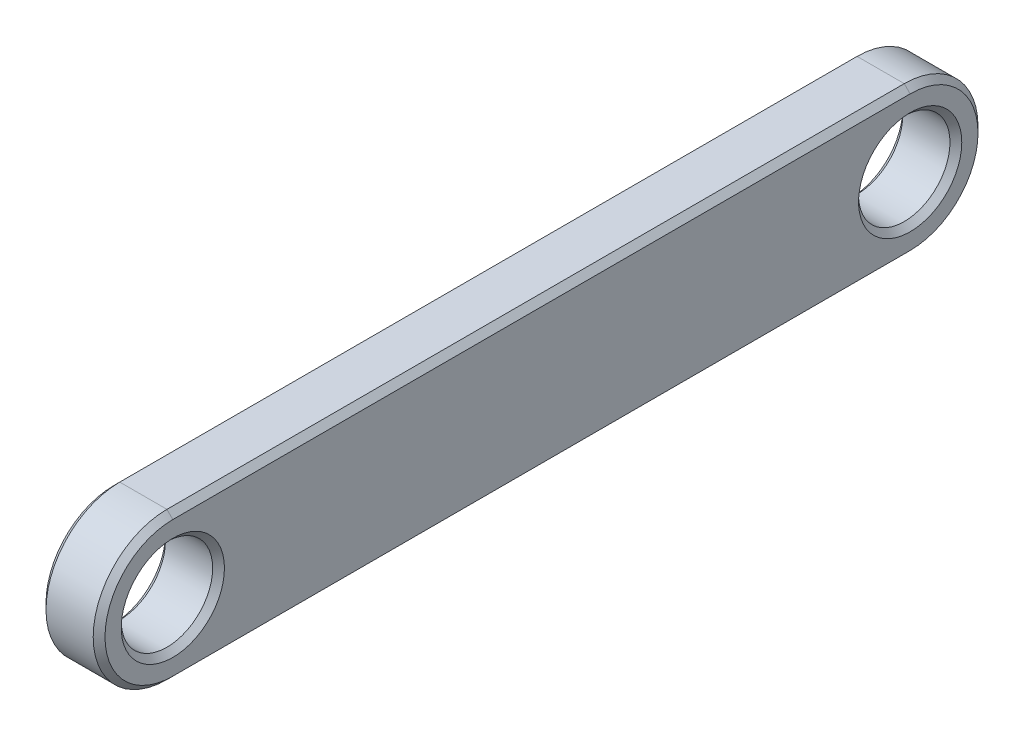
SolidWorks part; units mm, degrees
ref_plane "Front Plane" through (0, 0, 0) normal (0, 0, 1) x (1, 0, 0)
ref_plane "Top Plane" through (0, 0, 0) normal (0, 1, 0) x (1, 0, 0)
ref_plane "Right Plane" through (0, 0, 0) normal (1, 0, 0) x (0, 0, -1)
sketch "Sketch1" plane through (0, 0, 0) normal (1, 0, 0) x (0, 0, -1)
  line L0 (-12.5, 0) -> (12.5, 0) construction
  line L1 (-12.5, 2.5) -> (12.5, 2.5)
  line L2 (-12.5, -2.5) -> (12.5, -2.5)
  arc A0 (-12.5, 2.5) -> (-12.5, -2.5) centre (-12.5, 0) ccw
  arc A1 (12.5, -2.5) -> (12.5, 2.5) centre (12.5, 0) ccw
  circle A2 centre (-12.5, 0) radius 1.55
  circle A3 centre (12.5, 0) radius 1.55
  point P3 (0, 0)
  dimension "D1" = 3.1
  dimension "D2" = 3.1
  dimension "D4" = 2.5
  dimension "D3" = 25
extrude "Boss-Extrude1" add sketch "Sketch1" along normal blind 2
chamfer "Chamfer1" distance 0.2 angle 45 12 edges at (0, 0, -14.05) (0, 0, 10.95) (0, -2.5, 0) (0, 0, -15) (0, 2.5, 0) (0, 0, 15) (2, 0, -14.05) (2, 2.5, 0) (2, 0, -15) (2, -2.5, 0) (2, 0, 15) (2, 0, 10.95)
